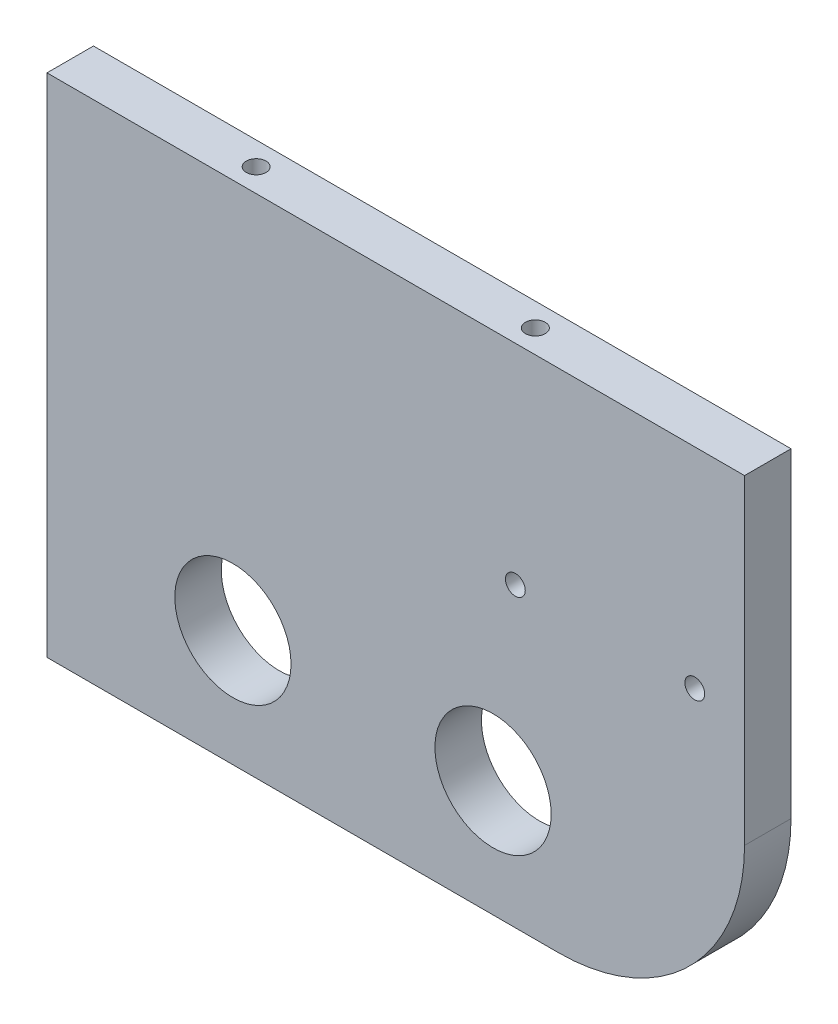
SolidWorks part; units mm, degrees
ref_plane "Front Plane" through (0, 0, 0) normal (0, 0, 1) x (1, 0, 0)
ref_plane "Top Plane" through (0, 0, 0) normal (0, 1, 0) x (1, 0, 0)
ref_plane "Right Plane" through (0, 0, 0) normal (1, 0, 0) x (0, 0, -1)
sketch "Sketch1" plane through (0, 0, -95.0394) normal (0, 0, 1) x (1, 0, 0)
  line L0 (34.3543, -15.875) -> (34.3543, 53.2785) construction
  line L1 (-60.9331, 53.2785) -> (34.3543, 53.2785) construction
  line L2 (-60.9331, -15.875) -> (-60.9331, 53.2785) construction
  line L3 (-60.9331, -15.875) -> (34.3543, -15.875) construction
  line L4 (34.3543, -15.875) -> (34.3543, 53.2785)
  line L5 (-60.9331, 53.2785) -> (34.3543, 53.2785)
  line L6 (-60.9331, -15.875) -> (-60.9331, 53.2785)
  line L7 (-60.9331, -15.875) -> (34.3543, -15.875)
  circle A1 centre (0, 0) radius 7.9375 construction
  circle A2 centre (-35.5331, 0) radius 7.9375 construction
  circle A4 centre (0, 0) radius 7.9375
  circle A5 centre (-35.5331, 0) radius 7.9375
extrude "Boss-Extrude1" add sketch "Sketch1" against normal blind 6.35
fillet "Fillet1" radius 25.4 1 edges at (34.3543, -15.875, -98.2144)
hole_wizard "#6-32 Tapped Hole1" positions "Sketch4" profile "Sketch5" tap size "#6-32" standard "ANSI Inch"
sketch "Sketch4" plane through (0, 0, -95.0394) normal (0, 0, 1) x (1, 0, 0)
  point P0 (27.5598, 24.7035)
  point P3 (3.0488, 24.7035)
sketch "Sketch5" plane through (27.5598, 24.7035, -95.0394) normal (1, 0, 0) x (0, -1, 0)
  line L0 (0, 0) -> (0, 11.7855)
  line L1 (0, 11.7855) -> (1.3525, 10.9728)
  line L2 (1.3525, 10.9728) -> (1.3525, 0)
  line L5 (1.3525, 0) -> (0, 0)
  line L10 (0, 11.7855) -> (-1.3525, 10.9728) construction
  line L11 (0, -6.35) -> (0, 107.95) construction
  dimension "Tap Drill Dia." = 2.7051
  dimension "Tap Drill Depth" = 10.9728
  dimension "Drill Angle" = 118
cosmetic thread "Hole Thread1" parameters "D1"=6.35, "D2"=3.5052
cosmetic thread "Hole Thread2" parameters "D1"=6.35, "D2"=3.5052
hole_wizard "#6-32 Tapped Hole2" positions "Sketch6" profile "Sketch7" tap size "#6-32" standard "ANSI Inch"
sketch "Sketch6" plane through (0, 53.2785, 0) normal (0, 1, 0) x (1, 0, 0)
  line L0 (-60.9331, 98.2144) -> (34.3543, 98.2144) construction
  line L1 (-60.9331, 101.3894) -> (-60.9331, 95.0394) construction
  line L2 (34.3543, 101.3894) -> (34.3543, 95.0394) construction
  point P0 (-35.5331, 98.2144)
  point P2 (2.6043, 98.2144)
  dimension "D1" = 25.4
  dimension "D2" = 31.75
sketch "Sketch7" plane through (-35.5331, 53.2785, -98.2144) normal (1, 0, 0) x (0, 0, 1)
  line L0 (0, 0) -> (0, 10.2107)
  line L1 (0, 10.2107) -> (1.3525, 9.398)
  line L2 (1.3525, 9.398) -> (1.3525, 0)
  line L5 (1.3525, 0) -> (0, 0)
  line L10 (0, 10.2107) -> (-1.3526, 9.398) construction
  line L11 (0, -6.35) -> (0, 107.95) construction
  dimension "Tap Drill Dia." = 2.7051
  dimension "Tap Drill Depth" = 9.398
  dimension "Drill Angle" = 118
cosmetic thread "Hole Thread3" parameters "D1"=7.0104, "D2"=3.5052
cosmetic thread "Hole Thread4" parameters "D1"=7.0104, "D2"=3.5052
hole_wizard "#6-32 Tapped Hole3" positions "Sketch8" profile "Sketch9" tap size "#6-32" standard "ANSI Inch"
sketch "Sketch8" plane through (-60.9331, 0, 0) normal (-1, 0, 0) x (0, 0, 1)
  line L0 (-98.2144, -15.875) -> (-98.2144, 53.2785) construction
  line L1 (-101.3894, -15.875) -> (-95.0394, -15.875) construction
  point P0 (-98.2144, 45.341)
  point P2 (-98.2144, 6.35)
  dimension "D1" = 7.9375
  dimension "D2" = 22.225
sketch "Sketch9" plane through (-60.9331, 45.341, -98.2144) normal (0, 1, 0) x (0, 0, 1)
  line L0 (0, 0) -> (0, 10.2107)
  line L1 (0, 10.2107) -> (1.3525, 9.398)
  line L2 (1.3525, 9.398) -> (1.3525, 0)
  line L5 (1.3525, 0) -> (0, 0)
  line L10 (0, 10.2107) -> (-1.3525, 9.398) construction
  line L11 (0, -6.35) -> (0, 107.95) construction
  dimension "Tap Drill Dia." = 2.7051
  dimension "Tap Drill Depth" = 9.398
  dimension "Drill Angle" = 118
cosmetic thread "Hole Thread5" parameters "D1"=7.0104, "D2"=3.5052
cosmetic thread "Hole Thread6" parameters "D1"=7.0104, "D2"=3.5052
